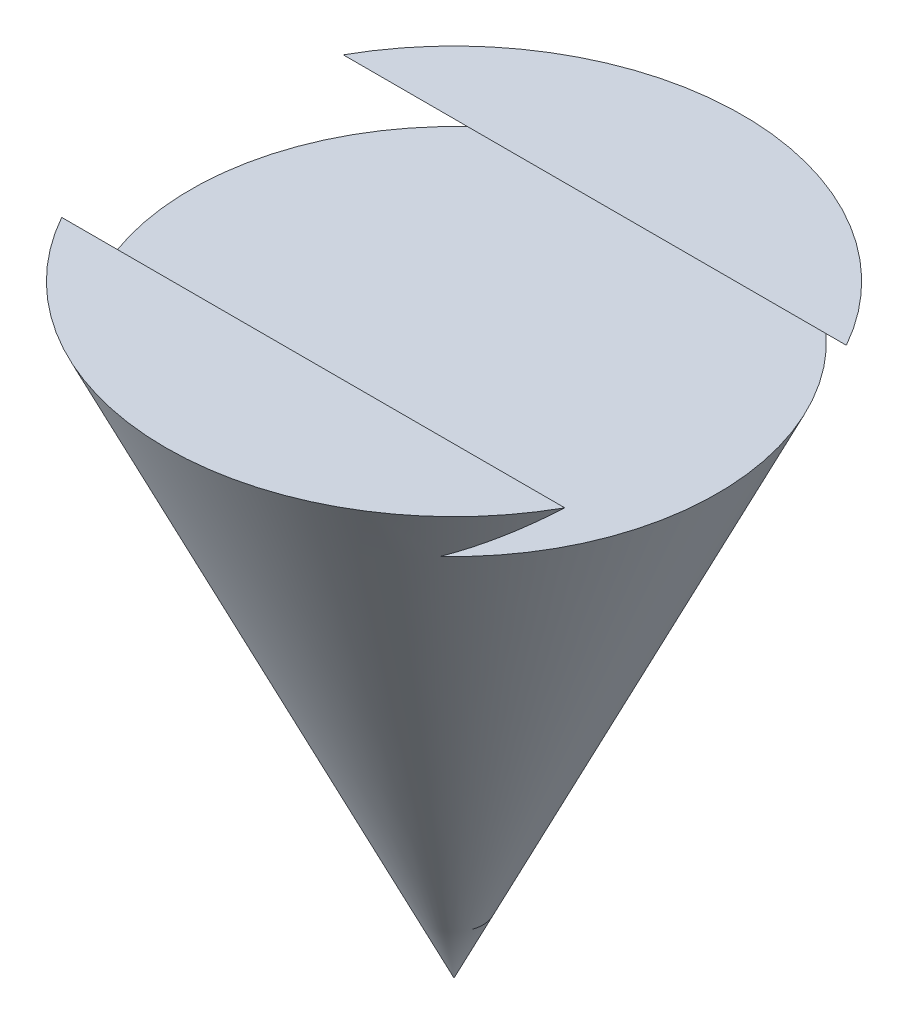
SolidWorks part; units mm, degrees
ref_plane "Front Plane" through (0, 0, 0) normal (0, 0, 1) x (1, 0, 0)
ref_plane "Top Plane" through (0, 0, 0) normal (0, 1, 0) x (1, 0, 0)
ref_plane "Right Plane" through (0, 0, 0) normal (1, 0, 0) x (0, 0, -1)
sketch "Sketch1" plane through (0, 0, 0) normal (1, 0, 0) x (0, 0, -1)
  line L0 (0, 0) -> (0, -45)
  line L1 (0, -45) -> (21.5, 0)
  line L2 (21.5, 0) -> (0, 0)
  dimension "D1" = 21.5
  dimension "D2" = 45
revolve "Revolve1" add sketch "Sketch1" angle 360 about L0
sketch "Sketch2" plane through (0, 0, 0) normal (1, 0, 0) x (0, 0, -1)
  line L0 (0, 0) -> (10.5, 0)
  line L1 (23.65, 0) -> (-23.65, 0) construction
  line L5 (-10.5, 0) -> (0, 0)
  line L6 (-10.5, 0) -> (-14.3891, -3.8891)
  line L7 (-14.3891, -3.8891) -> (14.3891, -3.8891)
  line L8 (14.3891, -3.8891) -> (10.5, 0)
  dimension "D1" = 10.5
  dimension "D2" = 10.5
  dimension "D3" = 5.5
  dimension "D4" = 45
  dimension "D5" = 5.5
extrude "Cut-Extrude1" cut sketch "Sketch2" against normal through all both and the other way through all
